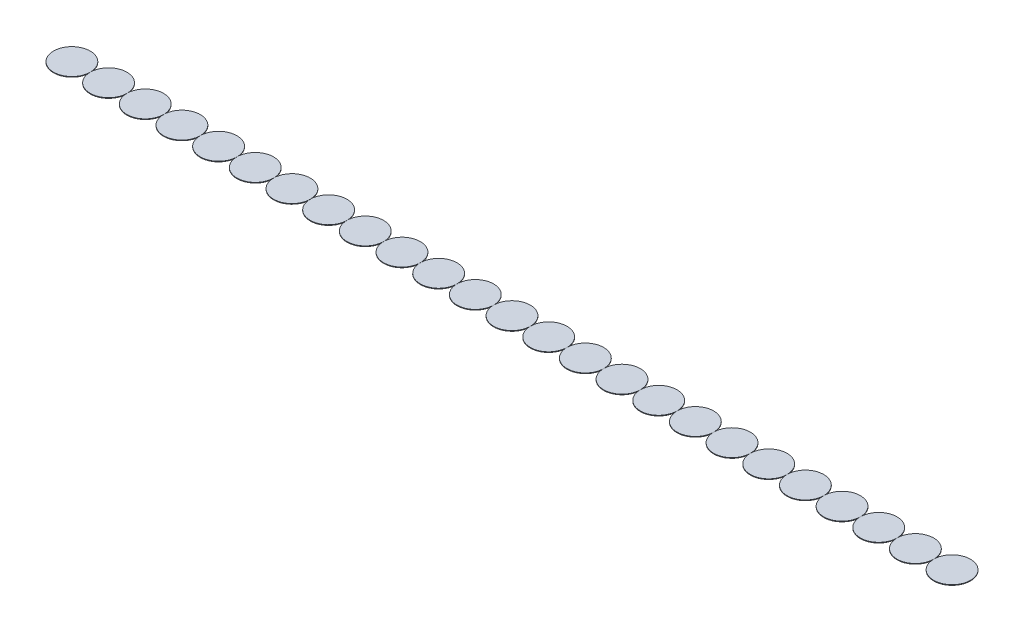
SolidWorks part; units mm, degrees
ref_plane "Front Plane" through (0, 0, 0) normal (0, 0, 1) x (1, 0, 0)
ref_plane "Top Plane" through (0, 0, 0) normal (0, 1, 0) x (1, 0, 0)
ref_plane "Right Plane" through (0, 0, 0) normal (1, 0, 0) x (0, 0, -1)
sketch "Sketch1" plane through (0, 0, 0) normal (0, 1, 0) x (1, 0, 0)
  line L0 (0, 0) -> (31, 0) construction
  line L1 (0, 0) -> (62, 0) construction
  line L2 (62, 0) -> (124, 0) construction
  line L3 (124, 0) -> (186, 0) construction
  line L4 (186, 0) -> (248, 0) construction
  line L5 (310, 0) -> (341, 0) construction
  line L6 (310, 0) -> (372, 0) construction
  line L7 (372, 0) -> (434, 0) construction
  line L8 (434, 0) -> (496, 0) construction
  line L9 (496, 0) -> (558, 0) construction
  line L10 (620, 0) -> (651, 0) construction
  line L11 (620, 0) -> (682, 0) construction
  line L12 (682, 0) -> (744, 0) construction
  line L13 (744, 0) -> (806, 0) construction
  line L14 (806, 0) -> (868, 0) construction
  line L15 (930, 0) -> (961, 0) construction
  line L16 (930, 0) -> (992, 0) construction
  line L17 (992, 0) -> (1054, 0) construction
  line L18 (1054, 0) -> (1116, 0) construction
  line L19 (1116, 0) -> (1178, 0) construction
  line L20 (1240, 0) -> (1271, 0) construction
  line L21 (1240, 0) -> (1302, 0) construction
  line L22 (1302, 0) -> (1364, 0) construction
  line L23 (1364, 0) -> (1426, 0) construction
  line L24 (1426, 0) -> (1488, 0) construction
  circle A0 centre (0, 0) radius 31
  circle A1 centre (62, 0) radius 31
  circle A2 centre (124, 0) radius 31
  circle A3 centre (186, 0) radius 31
  circle A4 centre (248, 0) radius 31
  circle A5 centre (310, 0) radius 31
  circle A6 centre (372, 0) radius 31
  circle A7 centre (434, 0) radius 31
  circle A8 centre (496, 0) radius 31
  circle A9 centre (558, 0) radius 31
  circle A10 centre (620, 0) radius 31
  circle A11 centre (682, 0) radius 31
  circle A12 centre (744, 0) radius 31
  circle A13 centre (806, 0) radius 31
  circle A14 centre (868, 0) radius 31
  circle A15 centre (930, 0) radius 31
  circle A16 centre (992, 0) radius 31
  circle A17 centre (1054, 0) radius 31
  circle A18 centre (1116, 0) radius 31
  circle A19 centre (1178, 0) radius 31
  circle A20 centre (1240, 0) radius 31
  circle A21 centre (1302, 0) radius 31
  circle A22 centre (1364, 0) radius 31
  circle A23 centre (1426, 0) radius 31
  circle A24 centre (1488, 0) radius 31
  dimension "D1" = 5
extrude "Boss-Extrude1" add sketch "Sketch1" along normal blind 1 contours A0 | A1 | A2 | A3 | A4 | A5 | A6 | A7 | A8 | A9 | A10 | A11 | A12 | A13 | A14 | A15 | A16 | A17 | A18 | A19 | A20 | A21 | A22 | A23 | A24
